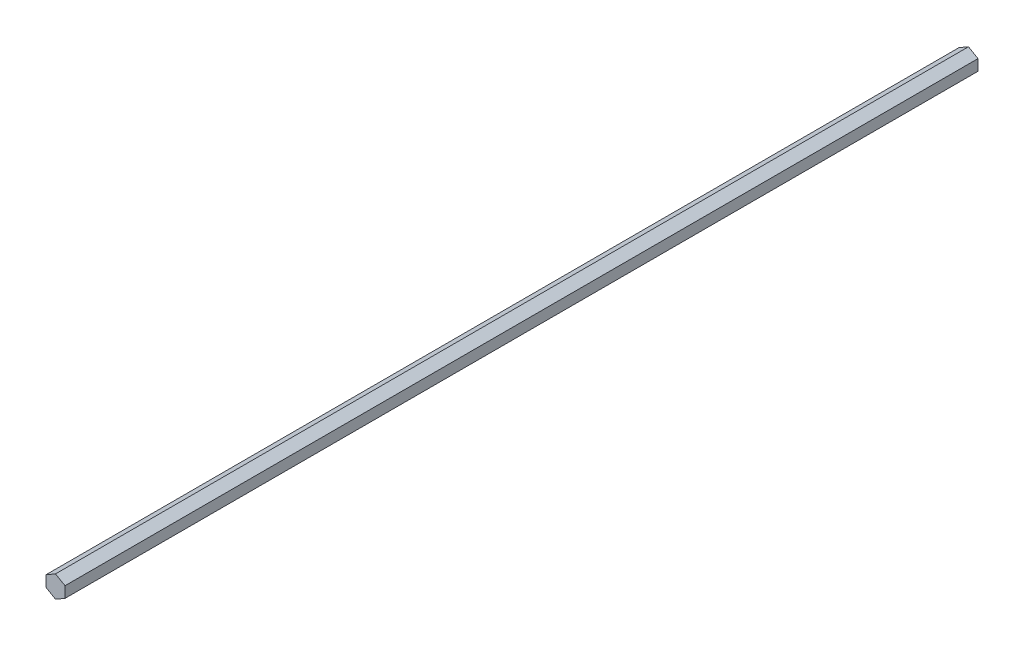
SolidWorks part; units mm, degrees
ref_plane "Front Plane" through (0, 0, 0) normal (0, 0, 1) x (1, 0, 0)
ref_plane "Top Plane" through (0, 0, 0) normal (0, 1, 0) x (1, 0, 0)
ref_plane "Right Plane" through (0, 0, 0) normal (1, 0, 0) x (0, 0, -1)
sketch "Sketch1" plane through (0, 0, 0) normal (0, 0, 1) x (1, 0, 0)
  line L0 (-6.35, 0) -> (6.35, 0) construction
  line L9 (0, 7.3323) -> (-6.35, 3.6662) construction
  line L10 (-6.35, 3.6662) -> (-6.35, -3.6662) construction
  line L11 (-6.35, -3.6662) -> (0, -7.3323) construction
  line L12 (0, -7.3323) -> (6.35, -3.6662) construction
  line L13 (6.35, -3.6662) -> (6.35, 3.6662) construction
  line L14 (6.35, 3.6662) -> (0, 7.3323) construction
  circle A3 centre (0, 0) radius 6.35 construction
  point P4 (0, 0)
  dimension "Width" = 12.7
sketch "Sketch2" plane through (0, 0, 0) normal (1, 0, 0) x (0, 0, -1)
  line L0 (304.8, 7.3323) -> (-304.8, 7.3323) construction
  point P3 (-290.195, 7.3323)
  point P4 (0, 7.3323)
  point P5 (290.195, 7.3323)
  dimension "Length" = 609.6
  dimension "D1" = 14.605
  dimension "D2" = 14.605
sketch "Sketch3" plane through (0, 0, 0) normal (0, 0, 1) x (1, 0, 0)
  line L1 (0, 7.3323) -> (6.35, 3.6662)
  line L2 (6.35, 3.6662) -> (6.35, -3.6662)
  line L3 (6.35, -3.6662) -> (0, -7.3323)
  line L4 (0, -7.3323) -> (-6.35, -3.6662)
  line L5 (-6.35, -3.6662) -> (-6.35, 3.6662)
  line L6 (-6.35, 3.6662) -> (0, 7.3323)
extrude "Boss-Extrude1" add sketch "Sketch3" along normal mid plane 609.6
equation "\"D1@Boss-Extrude1\" = \"Length@Sketch2\""
equation "\"D1@Sketch2\"=\"Width@Sketch1\"*1.15"
equation "\"D2@Sketch2\"=\"D1@Sketch2\""
